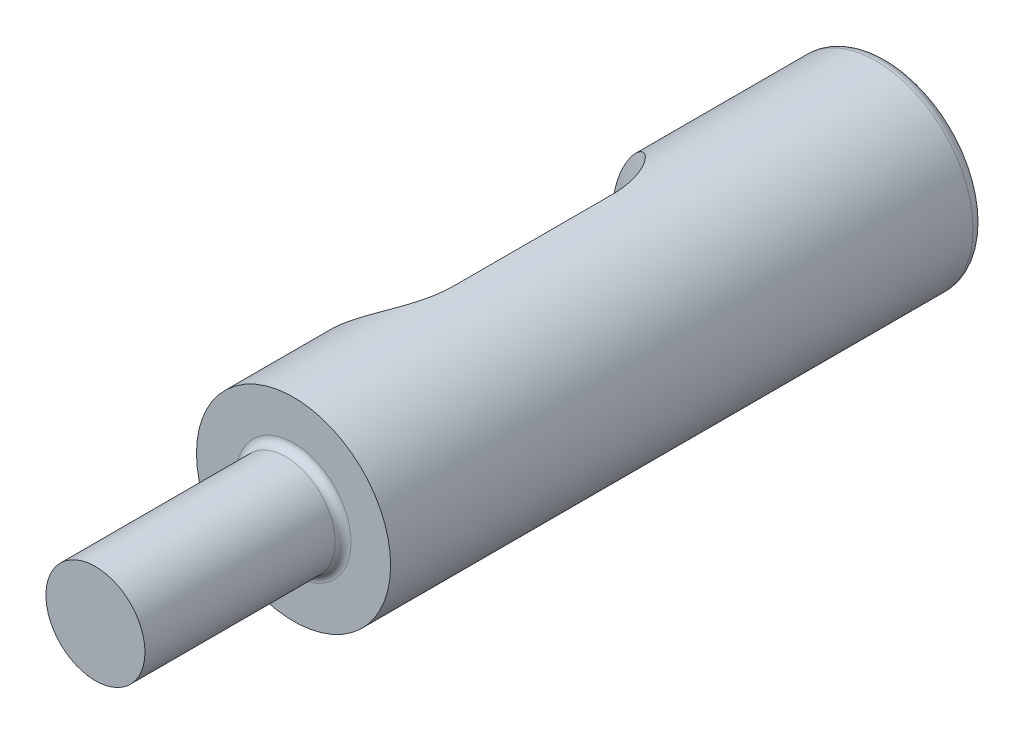
SolidWorks part; units mm, degrees
ref_plane "정면" through (0, 0, 0) normal (0, 0, 1) x (1, 0, 0)
ref_plane "윗면" through (0, 0, 0) normal (0, 1, 0) x (1, 0, 0)
ref_plane "우측면" through (0, 0, 0) normal (1, 0, 0) x (0, 0, -1)
sketch "스케치1" plane through (0, 0, 0) normal (0, 0, 1) x (1, 0, 0)
  circle A0 centre (0, 0) radius 2.45
  dimension "D1" = 4.9
extrude "보스-돌출1" add sketch "스케치1" along normal blind 15
sketch "스케치2" plane through (0, 0, 0) normal (0, 1, 0) x (1, 0, 0)
  line L0 (-2.45, 0) -> (-2.45, -15) construction
  line L1 (-2.45, -10.5) -> (-2.45, -1.6635) construction
  line L2 (-4.45, -6.5) -> (-4.45, -10.5)
  line L3 (-0.45, -6.5) -> (-0.45, -10.5)
  arc A0 (-4.45, -10.5) -> (-0.45, -10.5) centre (-2.45, -10.5) ccw
  arc A1 (-0.45, -6.5) -> (-4.45, -6.5) centre (-2.45, -6.5) ccw
  point P1 (-2.45, -4.5)
  dimension "D1" = 4
  dimension "D4" = 4
  dimension "D2" = 10.5
  dimension "D3" = 4
  dimension "D5" = 4
extrude "컷-돌출1" cut sketch "스케치2" against normal through all both and the other way through all
sketch "스케치3" plane through (0, 0, 15) normal (0, 0, 1) x (1, 0, 0)
  circle A0 centre (0, 0) radius 1.25
  dimension "D1" = 2.5
extrude "보스-돌출2" add sketch "스케치3" along normal blind 5
fillet "필렛1" radius 0.3 1 edges at (2.45, 0, 0)
fillet "필렛2" radius 0.2 1 edges at (1.25, 0, 15)
